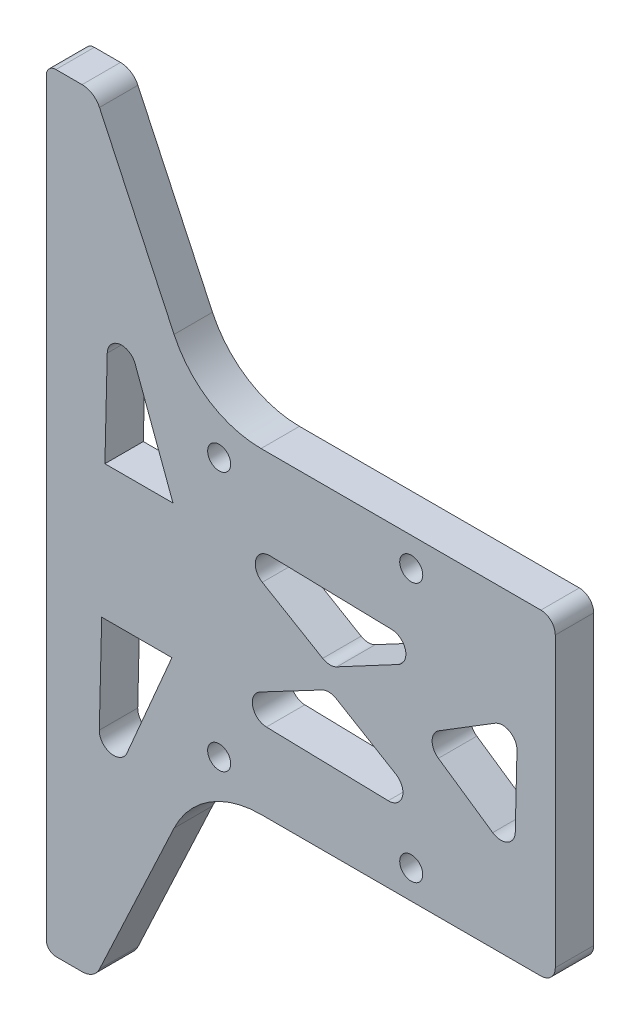
SolidWorks part; units mm, degrees
ref_plane "前视基准面" through (0, 0, 0) normal (0, 0, 1) x (1, 0, 0)
ref_plane "上视基准面" through (0, 0, 0) normal (0, 1, 0) x (1, 0, 0)
ref_plane "右视基准面" through (0, 0, 0) normal (1, 0, 0) x (0, 0, -1)
other "Configuration Table"
sketch "草图1" plane through (0, 0, 0) normal (0, 0, 1) x (1, 0, 0)
  line L0 (46.7231, 42.8869) -> (40.8876, 39.2897)
  line L1 (48.8308, 34.1043) -> (49.0098, 41.5741)
  line L2 (3.7279, 78.9776) -> (1, 78.9776)
  line L3 (0, 77.9776) -> (0, -0.0224)
  line L4 (1, -1.0224) -> (3.7279, -1.0224)
  line L5 (5.5393, 0.1297) -> (13.3035, 16.717)
  line L6 (22.3605, 22.4776) -> (51.5, 22.4776)
  line L7 (53, 23.9776) -> (53, 53.9776)
  line L8 (51.5, 55.4776) -> (22.3605, 55.4776)
  line L9 (13.3035, 61.2382) -> (5.5393, 77.8255)
  line L10 (40.8273, 36.7751) -> (46.4839, 32.9025)
  line L11 (35.9752, 45.9678) -> (23.2929, 46.2716)
  line L12 (30.2497, 39.7339) -> (36.6451, 43.1447)
  line L13 (22.4939, 43.4806) -> (28.7808, 39.7661)
  line L14 (28.7116, 36.879) -> (22.2541, 33.4698)
  line L15 (36.4051, 33.1277) -> (30.1804, 36.8407)
  line L16 (22.9185, 30.6437) -> (35.6008, 30.3399)
  line L17 (8.399, 21.0367) -> (15.6936, 38.078)
  line L18 (6.3448, 56.0753) -> (5.5204, 21.6629)
  line L19 (15.7203, 39.1918) -> (9.2501, 56.5629)
  line L20 (0, 93.865) -> (0, -74.3176) construction
  arc A0 (1, 78.9776) -> (0, 77.9776) centre (1, 77.9776) ccw
  arc A1 (0, -0.0224) -> (1, -1.0224) centre (1, -0.0224) ccw
  arc A2 (3.7279, -1.0224) -> (5.5393, 0.1297) centre (3.7279, 0.9776) ccw
  arc A3 (22.3605, 22.4776) -> (13.3035, 16.717) centre (22.3605, 12.4776) ccw
  arc A4 (51.5, 22.4776) -> (53, 23.9776) centre (51.5, 23.9776) ccw
  arc A5 (53, 53.9776) -> (51.5, 55.4776) centre (51.5, 53.9776) ccw
  arc A6 (13.3035, 61.2382) -> (22.3605, 55.4776) centre (22.3605, 65.4776) ccw
  arc A7 (5.5393, 77.8255) -> (3.7279, 78.9776) centre (3.7279, 76.9776) ccw
  arc A8 (49.0098, 41.5741) -> (46.7231, 42.8869) centre (47.5102, 41.61) ccw
  arc A9 (46.4839, 32.9025) -> (48.8308, 34.1043) centre (47.3312, 34.1402) ccw
  arc A10 (40.1751, 38.0487) -> (40.8273, 36.7751) centre (41.6747, 38.0128) ccw
  arc A11 (40.8876, 39.2897) -> (40.1751, 38.0487) centre (41.6747, 38.0128) ccw
  arc A12 (36.6451, 43.1447) -> (35.9752, 45.9678) centre (35.9392, 44.4682) ccw
  arc A13 (28.7808, 39.7661) -> (30.2497, 39.7339) centre (29.5438, 41.0575) ccw
  arc A14 (21.7574, 44.808) -> (22.4939, 43.4806) centre (23.257, 44.772) ccw
  arc A15 (23.2929, 46.2716) -> (21.7574, 44.808) centre (23.257, 44.772) ccw
  arc A16 (30.1804, 36.8407) -> (28.7116, 36.879) centre (29.4119, 35.5525) ccw
  arc A17 (35.6008, 30.3399) -> (36.4051, 33.1277) centre (35.6367, 31.8394) ccw
  arc A18 (21.4549, 32.1792) -> (22.9185, 30.6437) centre (22.9544, 32.1433) ccw
  arc A19 (22.2541, 33.4698) -> (21.4549, 32.1792) centre (22.9544, 32.1433) ccw
  arc A20 (5.5204, 21.6629) -> (8.399, 21.0367) centre (7.02, 21.6269) ccw
  arc A21 (9.2501, 56.5629) -> (6.3448, 56.0753) centre (7.8444, 56.0393) ccw
  arc A22 (15.6936, 38.078) -> (15.7203, 39.1918) centre (14.3147, 38.6683) ccw
extrude "凸台-拉伸1" add sketch "草图1" along normal blind 11
sketch "草图2" plane through (0, 0, 11) normal (0, 0, 1) x (1, 0, 0)
  line L5 (53, 23.9776) -> (53, 53.9776) construction
  line L6 (22.3605, 22.4776) -> (51.5, 22.4776) construction
  line L8 (23, 22.4776) -> (23, 27.4776)
  line L9 (23, 27.4776) -> (53, 27.4776)
  line L11 (53, 38.9776) -> (-37.4568, 38.9776) construction
  line L13 (23, 50.4776) -> (53, 50.4776)
  line L14 (23, 55.4776) -> (23, 50.4776)
  line L24 (3.7279, 78.9776) -> (1, 78.9776)
  line L25 (0, 77.9776) -> (0, -0.0224)
  line L26 (1, -1.0224) -> (3.7279, -1.0224)
  line L27 (5.5393, 0.1297) -> (13.3035, 16.717)
  line L28 (22.3605, 22.4776) -> (51.5, 22.4776)
  line L29 (53, 23.9776) -> (53, 53.9776)
  line L30 (51.5, 55.4776) -> (22.3605, 55.4776)
  line L31 (13.3035, 61.2382) -> (5.5393, 77.8255)
  line L32 (3.7279, 78.9776) -> (1, 78.9776)
  line L33 (0, 77.9776) -> (0, -0.0224)
  line L34 (1, -1.0224) -> (3.7279, -1.0224)
  line L35 (5.5393, 0.1297) -> (13.3035, 16.717)
  line L36 (22.3605, 22.4776) -> (23, 22.4776)
  line L37 (53, 27.4776) -> (53, 50.4776)
  line L38 (23, 55.4776) -> (22.3605, 55.4776)
  line L39 (13.3035, 61.2382) -> (5.5393, 77.8255)
  arc A8 (5.5393, 77.8255) -> (3.7279, 78.9776) centre (3.7279, 76.9776) ccw
  arc A9 (1, 78.9776) -> (0, 77.9776) centre (1, 77.9776) ccw
  arc A10 (0, -0.0224) -> (1, -1.0224) centre (1, -0.0224) ccw
  arc A11 (3.7279, -1.0224) -> (5.5393, 0.1297) centre (3.7279, 0.9776) ccw
  arc A12 (22.3605, 22.4776) -> (13.3035, 16.717) centre (22.3605, 12.4776) ccw
  arc A13 (51.5, 22.4776) -> (53, 23.9776) centre (51.5, 23.9776) ccw
  arc A14 (53, 53.9776) -> (51.5, 55.4776) centre (51.5, 53.9776) ccw
  arc A15 (13.3035, 61.2382) -> (22.3605, 55.4776) centre (22.3605, 65.4776) ccw
  arc A16 (5.5393, 77.8255) -> (3.7279, 78.9776) centre (3.7279, 76.9776) ccw
  arc A17 (1, 78.9776) -> (0, 77.9776) centre (1, 77.9776) ccw
  arc A18 (0, -0.0224) -> (1, -1.0224) centre (1, -0.0224) ccw
  arc A19 (3.7279, -1.0224) -> (5.5393, 0.1297) centre (3.7279, 0.9776) ccw
  arc A20 (22.3605, 22.4776) -> (13.3035, 16.717) centre (22.3605, 12.4776) ccw
  arc A23 (13.3035, 61.2382) -> (22.3605, 55.4776) centre (22.3605, 65.4776) ccw
  dimension "D3" = 0
extrude "切除-拉伸1" cut sketch "草图2" against normal blind 7
sketch "草图3" plane through (0, 55.4776, 0) normal (0, 1, 0) x (1, 0, 0)
  line L0 (53, -11) -> (53, 0) construction
  line L1 (51.5, 0) -> (22.3605, 0) construction
  circle A0 centre (48, -8) radius 2.05
  circle A1 centre (28, -8) radius 2.05
  dimension "D1" = 4.1
  dimension "D2" = 5
  dimension "D4" = 8
  dimension "D3" = 2
extrude "切除-拉伸2" cut sketch "草图3" against normal blind 37
fillet "圆角1" radius 2 6 edges at (53, 27.4776, 7.5) (23, 27.4776, 7.5) (23, 22.4776, 7.5) (23, 50.4776, 7.5) (53, 50.4776, 7.5) (23, 55.4776, 7.5)
sketch "草图4" plane through (0, 0, 4) normal (0, 0, 1) x (1, 0, 0)
  line L0 (0, 38.9776) -> (68.8704, 38.9776) construction
  line L1 (0, 77.9776) -> (0, -0.0224) construction
  line L2 (16.1183, 31.9776) -> (3.8985, 31.9776)
  line L3 (16.1183, 38.9776) -> (3.8985, 38.9776)
  line L4 (16.1183, 31.9776) -> (16.1183, 45.9776)
  line L5 (16.1183, 45.9776) -> (3.8985, 45.9776)
  line L6 (3.8985, 31.9776) -> (3.8985, 45.9776)
  line M21 (15.6936, 38.078) -> (8.399, 21.0367)
  line M23 (5.5204, 21.6629) -> (6.3448, 56.0753)
  line M25 (9.2501, 56.5629) -> (15.7203, 39.1918)
  arc M26 (15.7203, 39.1918) -> (15.6936, 38.078) centre (14.3147, 38.6683) cw
  dimension "D1" = 7
extrude "凸台-拉伸2" add sketch "草图4" against normal blind 4 contours L5 L3 M25 M23 M26 | L3 L2 M26 M23 M21
sketch "草图5" plane through (0, 55.4776, 0) normal (0, 1, 0) x (1, 0, 0)
  line L0 (23, -4) -> (25, -4) construction
  line L1 (23, -4) -> (57.4615, -4)
  line L2 (23, -4) -> (23, -12.3457)
  line L3 (23, -12.3457) -> (57.4615, -12.3457)
  line L4 (57.4615, -4) -> (57.4615, -12.3457)
  line L5 (25, -4) -> (22.3605, -4) construction
extrude "切除-拉伸3" cut sketch "草图5" against normal blind 34
sketch "草图6" plane through (0, 0, 4) normal (0, 0, 1) x (1, 0, 0)
  line L0 (53, 23.9776) -> (53, 53.9776) construction
  line L1 (0, 38.9776) -> (83.1383, 38.9776) construction
  line L2 (0, 77.9776) -> (0, -0.0224) construction
  line L3 (51.5, 55.4776) -> (22.3605, 55.4776) construction
  circle A0 centre (38, 52.4776) radius 1.2
  circle A1 centre (18, 52.4776) radius 1.2
  circle A2 centre (18, 25.4776) radius 1.2
  circle A3 centre (38, 25.4776) radius 1.2
  dimension "D1" = 2.4
  dimension "D2" = 15
  dimension "D4" = 3
  dimension "D3" = 2
extrude "切除-拉伸4" cut sketch "草图6" against normal blind 10
